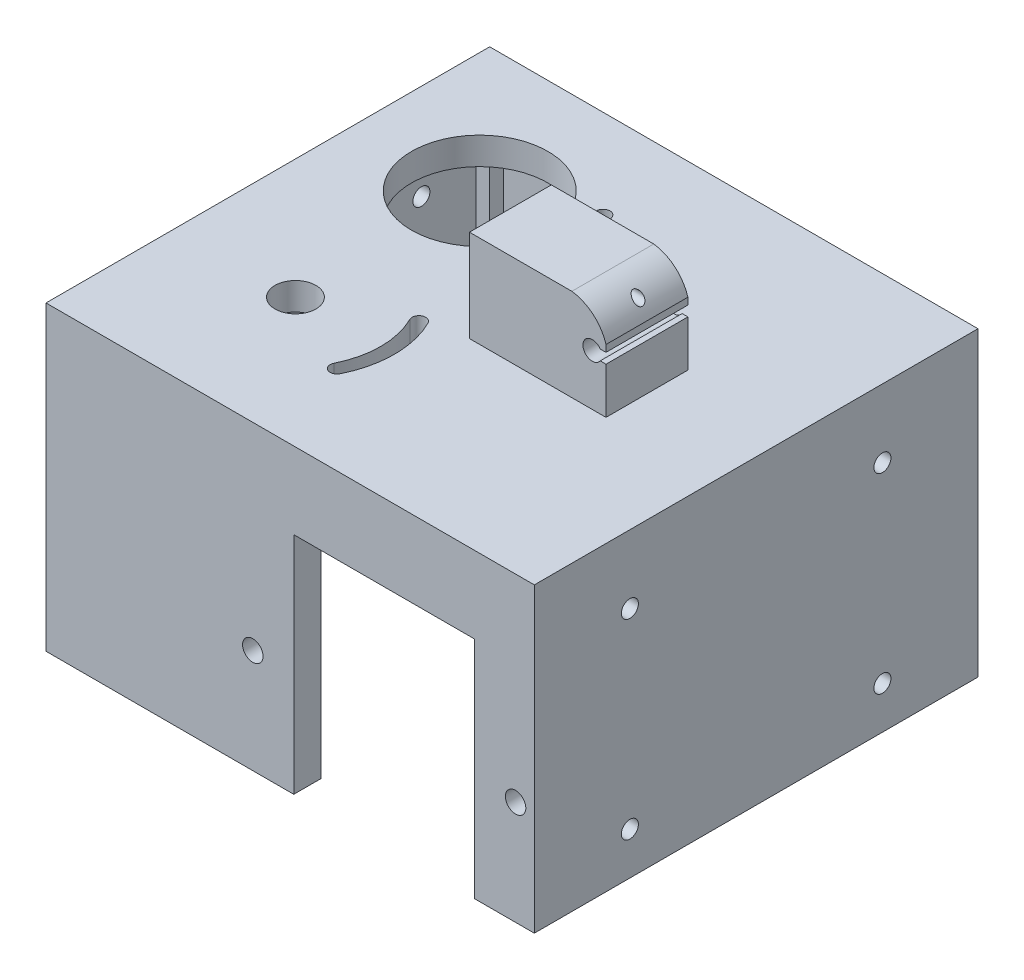
SolidWorks part; units mm, degrees
ref_plane "Front Plane" through (0, 0, 0) normal (0, 0, 1) x (1, 0, 0)
ref_plane "Top Plane" through (0, 0, 0) normal (0, 1, 0) x (1, 0, 0)
ref_plane "Right Plane" through (0, 0, 0) normal (1, 0, 0) x (0, 0, -1)
sketch "Sketch1" plane through (0, 0, 0) normal (0, 1, 0) x (1, 0, 0)
  line L0 (-55, 0) -> (55, 0) construction
  line L1 (-31, 40) -> (33, 40)
  line L2 (-31, 40) -> (-31, -10)
  line L3 (-31, -10) -> (33, -10)
  line L4 (33, 40) -> (33, -10)
  line L5 (0, -55) -> (0, 55) construction
  dimension "D1" = 64
  dimension "D2" = 50
  dimension "D3" = 40
  dimension "D4" = 31
extrude "Boss-Extrude1" add sketch "Sketch1" along normal blind 4
sketch "Sketch3" plane through (0, 4, 0) normal (0, 1, 0) x (1, 0, 0)
  line L0 (33, 40) -> (-31, 40) construction
  line L1 (-31, 40) -> (-31, -10) construction
  circle A0 centre (-21, 31) radius 6.5
  dimension "D1" = 13
  dimension "D2" = 9
  dimension "D3" = 10
extrude "Cut-Extrude2" cut sketch "Sketch3" against normal blind 4
sketch "Sketch4" plane through (0, 4, 0) normal (0, 1, 0) x (1, 0, 0)
  line L0 (-31, 40) -> (-31, -10) construction
  line L1 (-3, 23.5) -> (17, 23.5)
  line L2 (-3, 23.5) -> (-3, 11.5)
  line L3 (-3, 11.5) -> (17, 11.5)
  line L4 (17, 23.5) -> (17, 11.5)
  line L5 (33, 40) -> (-31, 40) construction
  dimension "D1" = 20
  dimension "D2" = 12
  dimension "D3" = 28
  dimension "D4" = 16.5
extrude "Boss-Extrude2" add sketch "Sketch4" along normal blind 13.5
sketch "Sketch5" plane through (0, 0, -11.5) normal (0, 0, 1) x (1, 0, 0)
  line L0 (-3, 17.5) -> (17, 17.5) construction
  line L1 (17, 17.5) -> (17, 4) construction
  line L2 (17, 10.75) -> (16.1524, 10.75)
  line L3 (22.1967, 12.25) -> (19, 12.25)
  line L4 (22.1967, 12.25) -> (22.1967, 10.75)
  line L5 (22.1967, 10.75) -> (17, 10.75)
  line L7 (19, 12.25) -> (16.1524, 12.25)
  line L9 (17, 10.75) -> (17.5112, 10.75)
  arc A0 (16.1524, 12.25) -> (16.1524, 10.75) centre (15, 11.5) ccw
  dimension "D1" = 2.75
  dimension "D2" = 6
  dimension "D3" = 2
  dimension "D4" = 1.5
  dimension "D5" = 0.75
extrude "Cut-Extrude3" cut sketch "Sketch5" against normal through all both and the other way through all
sketch "Sketch6" plane through (0, 0, -11.5) normal (0, 0, 1) x (1, 0, 0)
  line L0 (12, 17.5) -> (17, 17.5)
  line L1 (17, 17.5) -> (17, 13.25)
  line L4 (-3, 17.5) -> (17, 17.5) construction
  line L5 (17, 17.5) -> (17, 12.25) construction
  arc A1 (12, 17.5) -> (17, 13.25) centre (11.1985, 11.4909) cw
  dimension "D1" = 1
  dimension "D2" = 0
  dimension "D3" = 0
  dimension "D4" = 5
extrude "Cut-Extrude4" cut sketch "Sketch6" against normal through all both and the other way through all
sketch "Sketch7" plane through (-3, 0, 0) normal (-1, 0, 0) x (0, 0, 1)
  line L0 (-11.5, 17.5) -> (-11.5, 4) construction
  line L1 (-23.5, 17.5) -> (-11.5, 17.5) construction
  circle A0 centre (-17.5, 15.5) radius 0.75
  dimension "D1" = 1.5
  dimension "D2" = 6
  dimension "D3" = 2
extrude "Cut-Extrude5" cut sketch "Sketch7" against normal through all both and the other way through all
sketch "Sketch8" plane through (0, 4, 0) normal (0, 1, 0) x (1, 0, 0)
  line L0 (33, 40) -> (-31, 40) construction
  line L1 (-31, 40) -> (-31, -10) construction
  circle A0 centre (-7.5, 31) radius 1
  circle A1 centre (-7.5, 17.5) radius 1
  circle A2 centre (-7.5, 4) radius 1
  dimension "D3" = 2
  dimension "D1" = 9
  dimension "D2" = 23.5
  dimension "D5" = 27
  dimension "D4" = 3
extrude "Cut-Extrude6" cut sketch "Sketch8" against normal through all both and the other way through all
sketch "Sketch10" plane through (0, 4, 0) normal (0, 1, 0) x (1, 0, 0)
  line L0 (-31, 40) -> (-31, -10) construction
  circle A3 centre (-21, 4) radius 3
  circle A4 centre (-7.5, 4) radius 1 construction
  dimension "D1" = 0
  dimension "D3" = 6
  dimension "D2" = 10
extrude "Cut-Extrude7" cut sketch "Sketch10" against normal through all both and the other way through all
sketch "Sketch11" plane through (0, 4, 0) normal (0, 1, 0) x (1, 0, 0)
  line L22 (33, 40) -> (-31, 40) construction
  line L23 (-7.5, 17.5) -> (-17.9544, 17.5)
  arc A15 (-9.8024, 25.4444) -> (-9.8024, 36.5556) centre (-21, 31) ccw
  arc A16 (-8.0108, 24.5556) -> (-8.0108, 37.4444) centre (-21, 31) ccw
  arc A18 (-8.0108, 37.4444) -> (-9.8024, 36.5556) centre (-8.9066, 37) ccw
  arc A19 (-9.8024, 25.4444) -> (-8.0108, 24.5556) centre (-8.9066, 25) ccw
  arc A20 (-9.8024, 9.5556) -> (-9.8024, -1.5556) centre (-21, 4) cw
  arc A21 (-8.0108, -2.4444) -> (-9.8024, -1.5556) centre (-8.9066, -2) cw
  arc A22 (-8.0108, 10.4444) -> (-8.0108, -2.4444) centre (-21, 4) cw
  arc A23 (-9.8024, 9.5556) -> (-8.0108, 10.4444) centre (-8.9066, 10) cw
  dimension "D1" = 3
  dimension "D2" = 0
extrude "Cut-Extrude8" cut sketch "Sketch11" against normal through all both and the other way through all
sketch "Sketch12" plane through (0, 4, 0) normal (0, 1, 0) x (1, 0, 0)
  line L0 (33, -10) -> (33, 40) construction
  line L1 (-31, 40) -> (33, 40)
  line L2 (-31, 40) -> (-31, 45)
  line L3 (-31, 45) -> (33, 45)
  line L4 (33, 40) -> (33, 45)
  line L5 (-31, -10) -> (33, -10)
  line L6 (-31, -10) -> (-31, -15)
  line L7 (-31, -15) -> (33, -15)
  line L8 (33, -10) -> (33, -15)
  dimension "D1" = 0
  dimension "D2" = 0
  dimension "D3" = 5
  dimension "D4" = 5
extrude "Boss-Extrude3" add sketch "Sketch12" against normal blind 4
sketch "Sketch13" plane through (0, 0, 0) normal (0, 1, 0) x (1, 0, 0)
  line L1 (17, 23.5) -> (-3, 23.5) construction
  line L2 (33, -15) -> (33, 45) construction
  line L3 (33, 38.8531) -> (-31, 38.8531)
  line L4 (33, 38.8531) -> (33, 50.0031)
  line L5 (33, 50.0031) -> (-31, 50.0031)
  line L9 (-31, -15) -> (-38.5454, -15)
  line L10 (-31, -15) -> (-31, 38.8531)
  line L11 (-31, 50.0031) -> (-38.5454, 50.0031)
  line L12 (-38.5454, -15) -> (-38.5454, 50.0031)
  dimension "D1" = 11.15
  dimension "D2" = 15.3531
extrude "Boss-Extrude4" add sketch "Sketch13" along normal up to surface (4 mm away) up to face at (-8.4255, 4, -4)
sketch "Sketch14" plane through (0, 0, 0) normal (0, -1, 0) x (1, 0, 0)
  line L1 (-38.5454, 15) -> (-2.2454, 15)
  line L2 (-38.5454, 15) -> (-38.5454, 4.2)
  line L3 (-34.5454, 11) -> (-2.2454, 11)
  line L4 (-2.2454, 15) -> (-2.2454, 11)
  line L6 (33, 15) -> (33, -50.0031) construction
  line L7 (24.2546, 15) -> (33, 15)
  line L8 (24.2546, 15) -> (24.2546, 11)
  line L9 (24.2546, 11) -> (29, 11)
  line L10 (33, 15) -> (33, 4.2)
  line L12 (-38.5454, -50.0031) -> (-38.5454, 15) construction
  line L13 (33, -50.0031) -> (-38.5454, -50.0031) construction
  line L15 (-38.5454, 4.2) -> (-38.5454, -50.0031)
  line L16 (-38.5454, -50.0031) -> (-34.5454, -50.0031)
  line L17 (-34.5454, 11) -> (-34.5454, -46.0031)
  line L20 (33, 4.2) -> (33, -50.0031)
  line L21 (33, -50.0031) -> (29, -50.0031)
  line L22 (29, 11) -> (29, -46.0031)
  line L23 (29, -50.0031) -> (-34.5454, -50.0031)
  line L25 (29, -46.0031) -> (-34.5454, -46.0031)
  dimension "D1" = 4
  dimension "D2" = 4
  dimension "D3" = 36.3
  dimension "D4" = 4
  dimension "D5" = 26.5
  dimension "D6" = 4
extrude "Boss-Extrude5" add sketch "Sketch14" along normal blind 40.2
sketch "Sketch15" plane through (0, 0, -46.0031) normal (0, 0, 1) x (1, 0, 0)
  line L0 (29, 0) -> (-34.5454, 0) construction
  line L1 (29, 0) -> (-34.5454, 0) construction
  line L2 (29, -40.2) -> (29, 0) construction
  line L3 (29, -40.2) -> (29, 0) construction
  line L4 (24.2546, -40.2) -> (24.2546, 0) construction
  line L5 (24.2546, -6) -> (-15.7454, -6)
  line L6 (24.2546, -6) -> (24.2546, -30.2)
  line L7 (24.2546, -30.2) -> (-15.7454, -30.2)
  line L8 (-15.7454, -6) -> (-15.7454, -30.2)
  line L9 (-38.5454, 4) -> (33, 4) construction
  line L10 (29, -40.2) -> (-34.5454, -40.2) construction
  dimension "D3" = 40
  dimension "D1" = 10
  dimension "D2" = 10
sketch "Sketch17" plane through (0, 0, 0) normal (0, -1, 0) x (1, 0, 0)
  line L1 (24.2546, 15) -> (-2.2454, 15)
  line L2 (24.2546, 15) -> (24.2546, 11)
  line L3 (24.2546, 11) -> (-2.2454, 11)
  line L4 (-2.2454, 15) -> (-2.2454, 11)
extrude "Boss-Extrude7" add sketch "Sketch17" along normal blind 7.25
sketch "Sketch19" plane through (0, -40.2, 0) normal (0, -1, 0) x (1, 0, 0)
  line L1 (-38.5454, 15) -> (-32.5454, 15)
  line L2 (-38.5454, 15) -> (-38.5454, 4)
  line L3 (-38.5454, 4) -> (-32.5454, 4)
  line L4 (-32.5454, 15) -> (-32.5454, 4)
  line L6 (33, 15) -> (27, 15)
  line L7 (33, 15) -> (33, 4)
  line L8 (33, 4) -> (27, 4)
  line L9 (27, 15) -> (27, 4)
  line L11 (-38.5454, -50.0031) -> (-32.5454, -50.0031)
  line L12 (-38.5454, -50.0031) -> (-38.5454, -44.0031)
  line L13 (-38.5454, -44.0031) -> (-32.5454, -44.0031)
  line L14 (-32.5454, -50.0031) -> (-32.5454, -44.0031)
  line L15 (33, -50.0031) -> (27, -50.0031)
  line L16 (33, -50.0031) -> (33, -44.0031)
  line L17 (33, -44.0031) -> (27, -44.0031)
  line L18 (27, -50.0031) -> (27, -44.0031)
  dimension "D1" = 11
  dimension "D2" = 6
  dimension "D3" = 6
  dimension "D4" = 11
  dimension "D5" = 6
  dimension "D6" = 6
  dimension "D7" = 6
extrude "Boss-Extrude8" add sketch "Sketch19" against normal up to surface (40.2 mm away) up to face at (-8.4255, 0, -31)
sketch "Sketch18" plane through (0, -40.2, 0) normal (0, -1, 0) x (1, 0, 0)
  line L0 (-2.2454, 15) -> (-38.5454, 15) construction
  line L1 (-38.5454, 15) -> (-38.5454, -50.0031) construction
  line L2 (33, -50.0031) -> (33, 15) construction
  line L3 (-38.5454, -50.0031) -> (33, -50.0031) construction
  circle A0 centre (-35.5454, 7) radius 1.5
  circle A1 centre (30, 7) radius 1.5
  circle A2 centre (30, -47.0031) radius 1.5
  circle A3 centre (-35.5454, -47.0031) radius 1.5
  dimension "D1" = 3
  dimension "D2" = 8
  dimension "D3" = 3
  dimension "D6" = 3
  dimension "D7" = 3
  dimension "D4" = 2
  dimension "D5" = 2
extrude "Cut-Extrude9" cut sketch "Sketch18" against normal blind 4 and the other way through all
sketch "Sketch20" plane through (0, 0, 15) normal (0, 0, 1) x (1, 0, 0)
  line L0 (-2.2454, -40.2) -> (-38.5454, -40.2) construction
  line L1 (-2.2454, -40.2) -> (-2.2454, -7.25) construction
  line L2 (11.0046, -7.25) -> (11.0046, -22.3294)
  line L3 (24.2546, -7.25) -> (-2.2454, -7.25) construction
  circle A0 centre (-8.2454, -24.95) radius 1.5
  circle A1 centre (30.2546, -24.95) radius 1.5
  dimension "D2" = 3
  dimension "D1" = 15.25
  dimension "D3" = 6
extrude "Cut-Extrude10" cut sketch "Sketch20" against normal blind 4 and the other way through all contours A0 | A1
sketch "Sketch21" plane through (0, 0, -50.0031) normal (0, 0, -1) x (-1, 0, 0)
  line L0 (2.7727, 4) -> (2.7727, 13.7065)
  line L1 (-32.2273, 4) -> (37.7727, 4)
  line L2 (-32.2273, 4) -> (-32.2273, -46)
  line L3 (-32.2273, -46) -> (37.7727, -46)
  line L4 (37.7727, 4) -> (37.7727, -46)
  line L5 (-33, 4) -> (38.5454, 4) construction
  circle A0 centre (-14.2273, 0) radius 1.5
  circle A1 centre (-4.2273, 0) radius 1.5
  dimension "D7" = 3
  dimension "D8" = 3
  dimension "D1" = 70
  dimension "D2" = 35
  dimension "D3" = 50
  dimension "D4" = 0
  dimension "D5" = 18
  dimension "D6" = 4
  dimension "D9" = 4
  dimension "D10" = 10
extrude "Cut-Extrude11" cut sketch "Sketch21" against normal blind 4 contours A1 | A0
sketch "Sketch22" plane through (33, 0, 0) normal (1, 0, 0) x (0, 0, -1)
  line L0 (17.5, 4) -> (17.5, -12.7464)
  line L1 (11.5, 4) -> (23.5, 4) construction
  line L2 (-15, 4) -> (50.0031, 4) construction
  circle A0 centre (-1, -6) radius 1.25
  circle A1 centre (36, -6) radius 1.25
  circle A2 centre (36, -34) radius 1.25
  circle A3 centre (-1, -34) radius 1.25
  dimension "D1" = 2.5
  dimension "D4" = 18.5
  dimension "D5" = 10
  dimension "D2" = 2
  dimension "D3" = 2
extrude "Cut-Extrude12" cut sketch "Sketch22" against normal through all both and the other way through all contours A0 | A2 | A3 | A1
extrude "Cut-Extrude13" cut sketch "Sketch15" against normal blind 10
sketch "Sketch23" plane through (0, 4, 0) normal (0, 1, 0) x (1, 0, 0)
  circle A0 centre (-21, 31) radius 10
extrude "Cut-Extrude14" cut sketch "Sketch23" against normal through all
